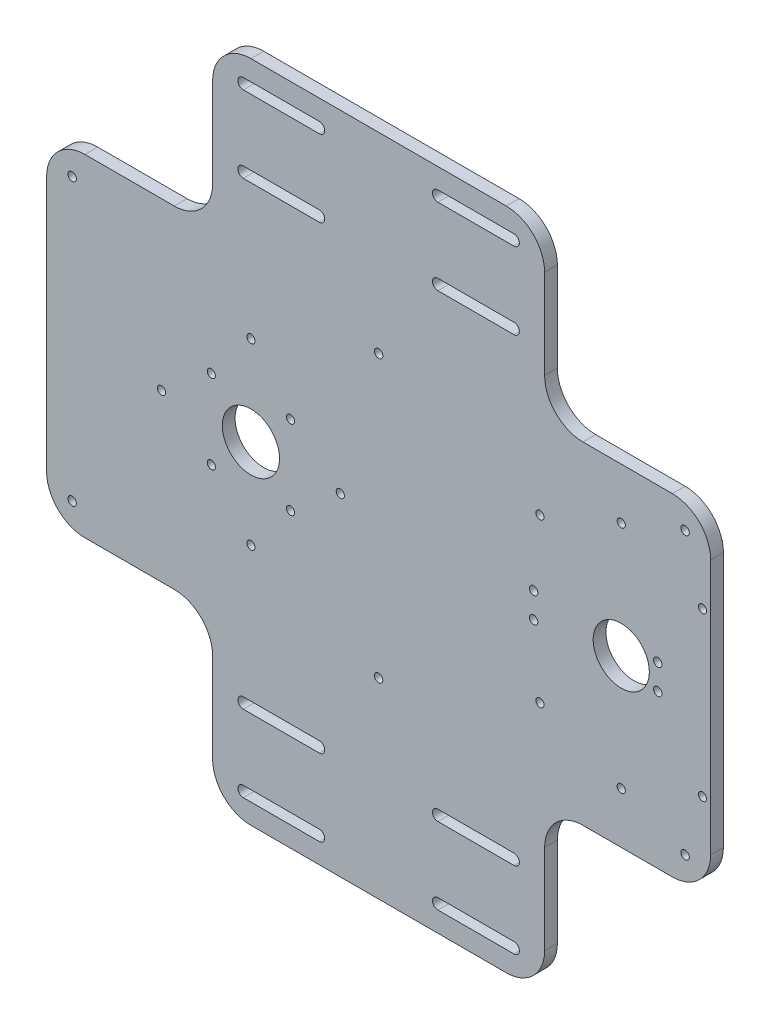
SolidWorks part; units mm, degrees
material "Thornel Mat VMA"
ref_plane "前视基准面" through (0, 0, 0) normal (0, 0, 1) x (1, 0, 0)
ref_plane "上视基准面" through (0, 0, 0) normal (0, 1, 0) x (1, 0, 0)
ref_plane "右视基准面" through (0, 0, 0) normal (1, 0, 0) x (0, 0, -1)
sketch "草图1" plane through (0, 0, 0) normal (0, 0, 1) x (1, 0, 0)
  line L1 (0, 0) -> (260, 0)
  line L2 (0, 0) -> (0, 260)
  line L3 (0, 260) -> (260, 260)
  line L4 (260, 0) -> (260, 260)
  line L5 (260, 260) -> (195, 260)
  line L6 (260, 260) -> (260, 195)
  line L7 (260, 195) -> (195, 195)
  line L8 (195, 260) -> (195, 195)
  line L9 (0, 260) -> (65, 260)
  line L10 (0, 260) -> (0, 195)
  line L11 (0, 195) -> (65, 195)
  line L12 (65, 260) -> (65, 195)
  line L13 (0, 0) -> (65, 0)
  line L14 (0, 0) -> (0, 65)
  line L15 (0, 65) -> (65, 65)
  line L16 (65, 0) -> (65, 65)
  line L17 (260, 0) -> (195, 0)
  line L18 (260, 0) -> (260, 65)
  line L19 (260, 65) -> (195, 65)
  line L20 (195, 0) -> (195, 65)
  dimension "D1" = 260
  dimension "D2" = 260
  dimension "D3" = 65
  dimension "D4" = 65
  dimension "D5" = 65
  dimension "D6" = 65
  dimension "D7" = 65
  dimension "D8" = 65
  dimension "D9" = 65
  dimension "D10" = 65
extrude "凸台-拉伸1" add sketch "草图1" along normal blind 5 contours L1 L20 L19 L4 L7 L8 L3 L12 L11 L2 L15 L16
sketch "草图2" plane through (0, 0, 0) normal (0, 0, -1) x (-1, 0, 0)
  line L0 (-130, 0) -> (-130, 260) construction
  line L1 (-65, 0) -> (-195, 0) construction
  line L2 (-65, 260) -> (-195, 260) construction
  line L3 (-260, 130) -> (0, 130) construction
  line L4 (-260, 65) -> (-260, 195) construction
  line L5 (0, 65) -> (0, 195) construction
  line L6 (-140, 10) -> (-65, 10) construction
  line L8 (-140, 40) -> (-114.3258, 40) construction
  line L9 (-106.8, 10) -> (-77, 10) construction
  line L10 (-106.8, 12.1) -> (-77, 12.1)
  line L11 (-106.8, 7.9) -> (-77, 7.9)
  line L12 (-106.8, 40) -> (-77, 40) construction
  line L13 (-106.8, 42.1) -> (-77, 42.1)
  line L14 (-106.8, 37.9) -> (-77, 37.9)
  line L15 (-65, 0) -> (-65, 65) construction
  line L16 (-153.2, 10) -> (-183, 10) construction
  line L17 (-153.2, 12.1) -> (-183, 12.1)
  line L18 (-153.2, 7.9) -> (-183, 7.9)
  line L19 (-153.2, 40) -> (-183, 40) construction
  line L20 (-153.2, 42.1) -> (-183, 42.1)
  line L21 (-153.2, 37.9) -> (-183, 37.9)
  line L22 (-106.8, 250) -> (-77, 250) construction
  line L23 (-106.8, 247.9) -> (-77, 247.9)
  line L24 (-106.8, 252.1) -> (-77, 252.1)
  line L25 (-106.8, 220) -> (-77, 220) construction
  line L26 (-106.8, 217.9) -> (-77, 217.9)
  line L27 (-106.8, 222.1) -> (-77, 222.1)
  line L28 (-153.2, 250) -> (-183, 250) construction
  line L29 (-153.2, 247.9) -> (-183, 247.9)
  line L30 (-153.2, 252.1) -> (-183, 252.1)
  line L31 (-153.2, 220) -> (-183, 220) construction
  line L32 (-153.2, 217.9) -> (-183, 217.9)
  line L33 (-153.2, 222.1) -> (-183, 222.1)
  arc A0 (-106.8, 12.1) -> (-106.8, 7.9) centre (-106.8, 10) ccw
  arc A1 (-77, 7.9) -> (-77, 12.1) centre (-77, 10) ccw
  arc A2 (-106.8, 42.1) -> (-106.8, 37.9) centre (-106.8, 40) ccw
  arc A3 (-77, 37.9) -> (-77, 42.1) centre (-77, 40) ccw
  arc A4 (-153.2, 12.1) -> (-153.2, 7.9) centre (-153.2, 10) cw
  arc A5 (-183, 7.9) -> (-183, 12.1) centre (-183, 10) cw
  arc A6 (-153.2, 42.1) -> (-153.2, 37.9) centre (-153.2, 40) cw
  arc A7 (-183, 37.9) -> (-183, 42.1) centre (-183, 40) cw
  arc A8 (-106.8, 247.9) -> (-106.8, 252.1) centre (-106.8, 250) cw
  arc A9 (-77, 252.1) -> (-77, 247.9) centre (-77, 250) cw
  arc A10 (-106.8, 217.9) -> (-106.8, 222.1) centre (-106.8, 220) cw
  arc A11 (-77, 222.1) -> (-77, 217.9) centre (-77, 220) cw
  arc A12 (-153.2, 247.9) -> (-153.2, 252.1) centre (-153.2, 250) ccw
  arc A13 (-183, 252.1) -> (-183, 247.9) centre (-183, 250) ccw
  arc A14 (-153.2, 217.9) -> (-153.2, 222.1) centre (-153.2, 220) ccw
  arc A15 (-183, 222.1) -> (-183, 217.9) centre (-183, 220) ccw
  point P18 (-91.9, 10)
  point P23 (-91.9, 40)
  point P34 (-168.1, 10)
  point P41 (-168.1, 40)
  point P48 (-91.9, 250)
  point P55 (-91.9, 220)
  point P62 (-168.1, 250)
  point P69 (-168.1, 220)
  dimension "D6" = 2.1
  dimension "D1" = 10
  dimension "D2" = 30
  dimension "D3" = 4.2
  dimension "D4" = 29.8
  dimension "D5" = 29.8
  dimension "D7" = 12
  dimension "D8" = 12
extrude "切除-拉伸1" cut sketch "草图2" against normal blind 5
sketch "草图3" plane through (0, 0, 5) normal (0, 0, 1) x (1, 0, 0)
  line L0 (0, 130) -> (260, 130) construction
  line L1 (0, 65) -> (0, 195) construction
  line L2 (260, 65) -> (260, 195) construction
  line L3 (130, 260) -> (130, 0) construction
  line L4 (65, 260) -> (195, 260) construction
  line L5 (65, 0) -> (195, 0) construction
  line L6 (250, 195) -> (250, 65) construction
  line L7 (260, 195) -> (195, 195) construction
  line L8 (260, 65) -> (195, 65) construction
  line L9 (10, 75) -> (250, 75) construction
  line L10 (10, 185) -> (250, 185) construction
  circle A0 centre (250, 185) radius 1.65
  circle A1 centre (250, 75) radius 1.65
  circle A2 centre (10, 75) radius 1.65
  circle A3 centre (10, 185) radius 1.65
  circle A4 centre (130, 75) radius 1.65
  circle A5 centre (130, 185) radius 1.65
  dimension "D2" = 3.3
  dimension "D4" = 3.3
  dimension "D5" = 3.3
  dimension "D1" = 10
  dimension "D3" = 10
extrude "切除-拉伸2" cut sketch "草图3" against normal blind 10
sketch "草图4" plane through (0, 0, 5) normal (0, 0, 1) x (1, 0, 0)
  line L0 (0, 130) -> (260, 130) construction
  line L1 (0, 65) -> (0, 195) construction
  line L2 (260, 65) -> (260, 195) construction
  line L3 (225, 130) -> (225, 183.4979) construction
  line L4 (190.7, 130) -> (190.7, 167.7695) construction
  line L5 (239.3, 130) -> (239.3, 162.2133) construction
  line L6 (80, 130) -> (80, 157.0741) construction
  line L7 (193.1802, 161.8198) -> (225, 130) construction
  circle A0 centre (80, 130) radius 11.2
  circle A1 centre (225, 130) radius 11
  circle A2 centre (190.7, 134.95) radius 1.65
  circle A3 centre (190.7, 125.05) radius 1.65
  circle A4 centre (239.3, 134.95) radius 1.65
  circle A5 centre (239.3, 125.05) radius 1.65
  circle A6 centre (64.5, 145.5) radius 1.6
  circle A7 centre (95.5, 145.5) radius 1.6
  circle A8 centre (95.5, 114.5) radius 1.6
  circle A9 centre (64.5, 114.5) radius 1.6
  circle A10 centre (225, 130) radius 45 construction
  circle A11 centre (193.1802, 161.8198) radius 1.6
  circle A14 centre (193.1802, 98.1802) radius 1.6
  circle A15 centre (80, 130) radius 35 construction
  circle A16 centre (115, 130) radius 1.6
  circle A17 centre (80, 95) radius 1.6
  circle A18 centre (45, 130) radius 1.6
  circle A19 centre (80, 165) radius 1.6
  circle A20 centre (256.8198, 161.8198) radius 1.6 [skipped]
  circle A21 centre (256.8198, 98.1802) radius 1.6 [skipped]
  circle A22 centre (225, 175) radius 1.6
  circle A23 centre (225, 85) radius 1.6
  circle A24 centre (256.8198, 98.1802) radius 1.6
  circle A25 centre (256.8198, 161.8198) radius 1.6
  point P37 (80, 130)
  point P47 (225, 130)
  point P57 (80, 130)
  dimension "D1" = 22.4
  dimension "D3" = 22
  dimension "D7" = 3.3
  dimension "D8" = 3.3
  dimension "D10" = 3.3
  dimension "D11" = 3.3
  dimension "D13" = 3.2
  dimension "D17" = 90
  dimension "D18" = 3.2
  dimension "D21" = 70
  dimension "D22" = 3.2
  dimension "D24" = 3.2
  dimension "D25" = 3.2
  dimension "D2" = 80
  dimension "D4" = 35
  dimension "D5" = 34.3
  dimension "D6" = 4.95
  dimension "D9" = 48.6
  dimension "D12" = 9.9
  dimension "D14" = 15.5
  dimension "D15" = 15.5
  dimension "D19" = 45
  dimension "D16" = 4
  dimension "D20" = 4
  dimension "D23" = 4
extrude "切除-拉伸3" cut sketch "草图4" against normal blind 10
fillet "圆角1" radius 15 12 edges at (260, 65, 2.5) (195, 65, 2.5) (195, 0, 2.5) (65, 0, 2.5) (65, 65, 2.5) (0, 65, 2.5) (0, 195, 2.5) (65, 195, 2.5) (65, 260, 2.5) (195, 260, 2.5) (195, 195, 2.5) (260, 195, 2.5)
